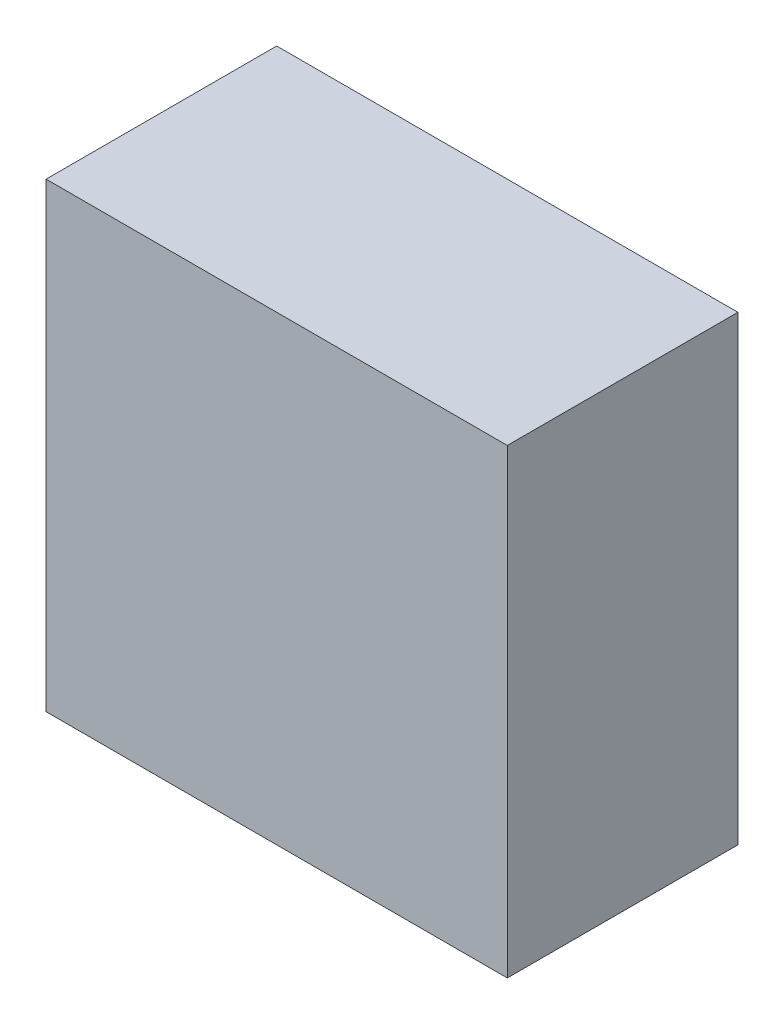
SolidWorks part; units mm, degrees
ref_plane "Front Plane" through (0, 0, 0) normal (0, 0, 1) x (1, 0, 0)
ref_plane "Top Plane" through (0, 0, 0) normal (0, 1, 0) x (1, 0, 0)
ref_plane "Right Plane" through (0, 0, 0) normal (1, 0, 0) x (0, 0, -1)
sketch "Sketch1" plane through (0, 0, 0) normal (0, 0, 1) x (1, 0, 0)
  line L1 (0, 0) -> (40, 0) construction
  line L2 (0, 0) -> (0, 40) construction
  line L3 (0, 40) -> (40, 40) construction
  line L4 (40, 0) -> (40, 40) construction
  line L5 (10, 10) -> (30, 10)
  line L6 (10, 10) -> (10, 30)
  line L7 (10, 30) -> (30, 30)
  line L8 (30, 10) -> (30, 30)
extrude "Boss-Extrude1" add sketch "Sketch1" along normal blind 10
